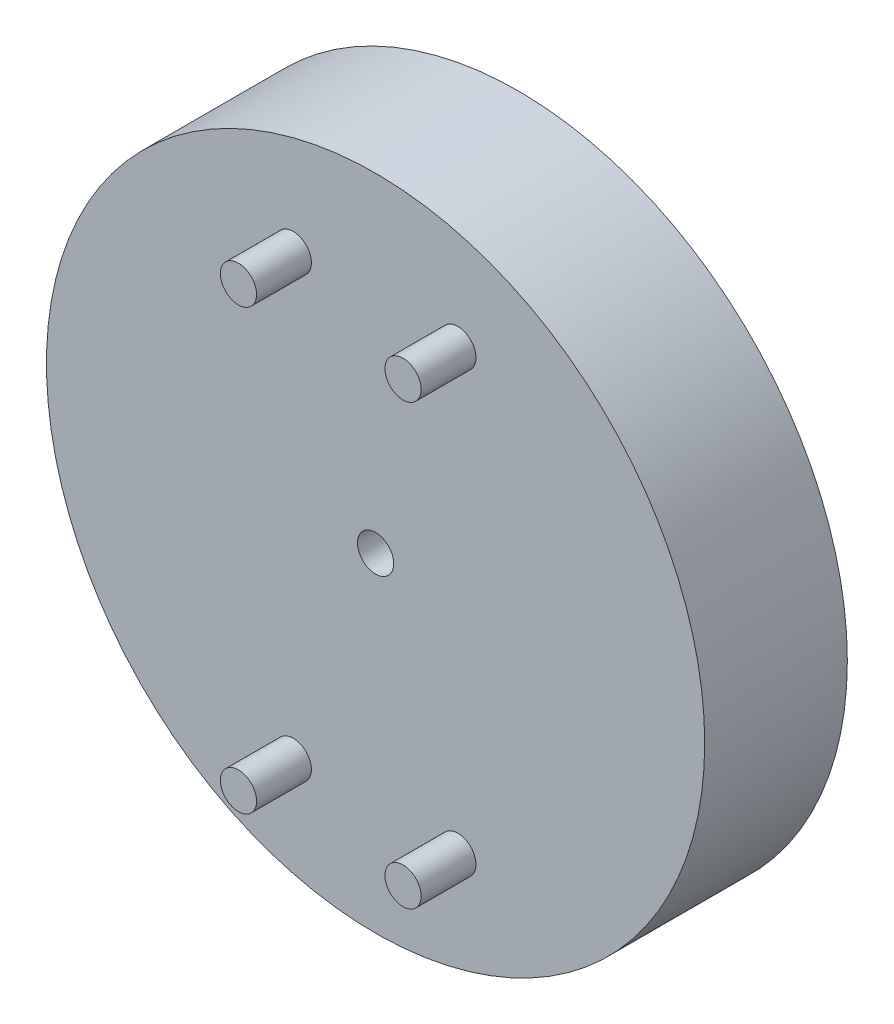
SolidWorks part; units mm, degrees
ref_plane "前视基准面" through (0, 0, 0) normal (0, 0, 1) x (1, 0, 0)
ref_plane "上视基准面" through (0, 0, 0) normal (0, 1, 0) x (1, 0, 0)
ref_plane "右视基准面" through (0, 0, 0) normal (1, 0, 0) x (0, 0, -1)
ref_plane "基准面1" through (0, 0, 6) normal (0, 0, 1) x (1, 0, 0)
sketch "草图1" plane through (0, 0, 6) normal (0, 0, 1) x (1, 0, 0)
  circle A0 centre (0, 0) radius 60
  circle A3 centre (0, 0) radius 3.3
  point P13 (21.562, 21.6386)
extrude "凸台-拉伸1" add sketch "草图1" against normal blind 26
sketch "草图2" plane through (0, 0, -20) normal (0, 0, -1) x (-1, 0, 0)
  line L1 (-15, -40) -> (15, -40) construction
  line L2 (-15, -40) -> (-15, 40) construction
  line L3 (-15, 40) -> (15, 40) construction
  line L4 (15, -40) -> (15, 40) construction
  line L5 (-15, -40) -> (15, 40) construction
  line L6 (-15, 40) -> (15, -40) construction
  circle A4 centre (-15, 40) radius 3.3
  circle A5 centre (15, 40) radius 3.3
  circle A6 centre (-15, -40) radius 3.3
  circle A7 centre (15, -40) radius 3.3
  point P16 (0, 0)
  dimension "D1" = 80
  dimension "D2" = 30
extrude "凸台-拉伸2" add sketch "草图2" against normal blind 36
